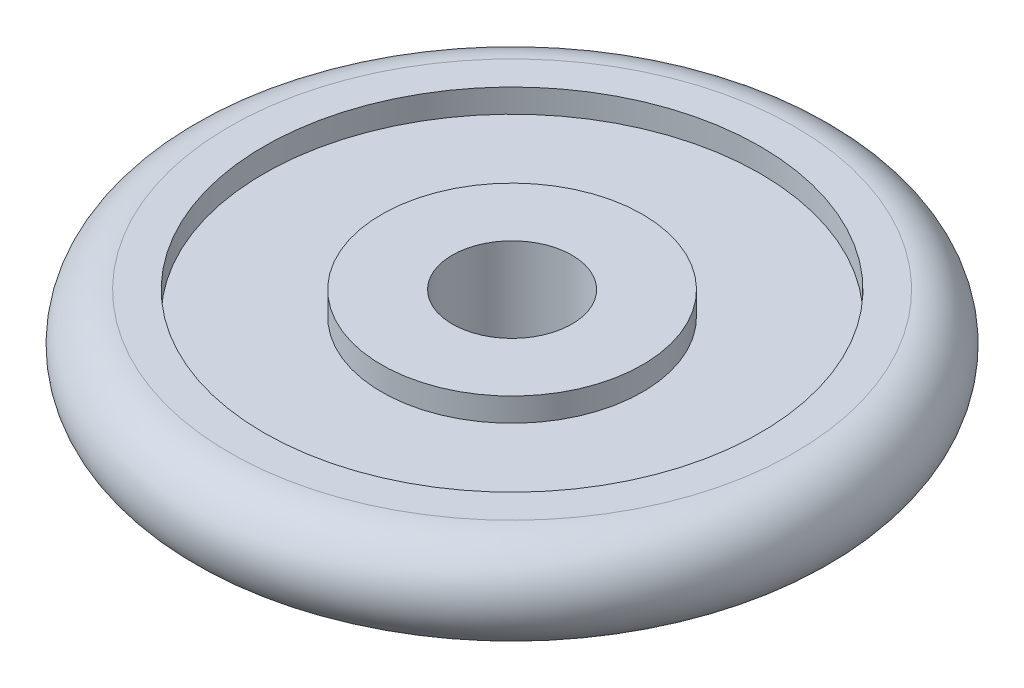
SolidWorks part; units mm, degrees
material "Fundición gris"
ref_plane "Alzado" through (0, 0, 0) normal (0, 0, 1) x (1, 0, 0)
ref_plane "Planta" through (0, 0, 0) normal (0, 1, 0) x (1, 0, 0)
ref_plane "Vista lateral" through (0, 0, 0) normal (1, 0, 0) x (0, 0, -1)
sketch "Croquis1" plane through (0, 0, 0) normal (0, 0, 1) x (1, 0, 0)
  line L0 (-12.7, 0) -> (12.7, 0) construction
  line L1 (12.7, -10) -> (12.7, 10)
  line L2 (12.7, 10) -> (27.7, 10)
  line L3 (27.7, 10) -> (27.7, 5)
  line L4 (27.7, 5) -> (52.7, 5)
  line L5 (52.7, 5) -> (52.7, 10)
  line L6 (52.7, 10) -> (60, 10)
  line L7 (12.7, 0) -> (60, 0) construction
  line L9 (12.7, -10) -> (27.7, -10)
  line L10 (27.7, -10) -> (27.7, -5)
  line L11 (27.7, -5) -> (52.7, -5)
  line L12 (52.7, -5) -> (52.7, -10)
  line L13 (52.7, -10) -> (60, -10)
  line L14 (0, 0) -> (0, 10) construction
  arc A0 (60, -10) -> (60, 10) centre (60, 0) ccw
  point P4 (0, 0)
  dimension "D2" = 20
  dimension "D1" = 25.4
  dimension "D3" = 10
  dimension "D4" = 15
  dimension "D5" = 60
  dimension "D6" = 5
  dimension "D7" = 5
  dimension "D8" = 25
revolve "Revolución1" add sketch "Croquis1" angle 360 about L14
